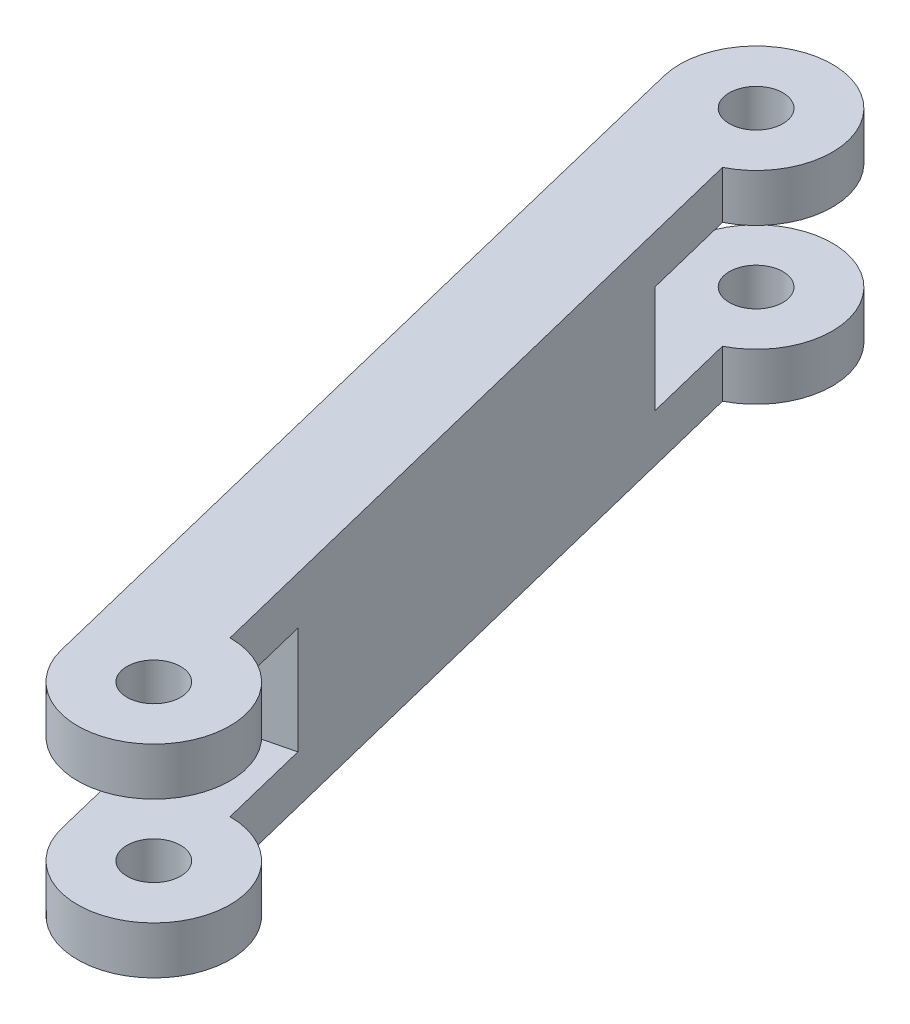
SolidWorks part; units mm, degrees
ref_plane "Front Plane" through (0, 0, 0) normal (0, 0, 1) x (1, 0, 0)
ref_plane "Top Plane" through (0, 0, 0) normal (0, 1, 0) x (1, 0, 0)
ref_plane "Right Plane" through (0, 0, 0) normal (1, 0, 0) x (0, 0, -1)
sketch "Sketch1" plane through (0, 0, 0) normal (0, 1, 0) x (1, 0, 0)
  line L0 (47.2297, 219.0186) -> (732.563, 219.0186) construction
  line L1 (-11.6924, 36.0113) -> (-3.4806, 2.5204)
  line L2 (-7.1402, 33.9178) -> (-0.3727, 6.4825)
  circle A0 centre (-8.5844, 36.7734) radius 1.125
  arc A1 (-7.1402, 33.9178) -> (-11.6924, 36.0113) centre (-8.5844, 36.7734) ccw
  circle A2 centre (-0.3727, 3.2825) radius 1.125
  arc A3 (-3.4806, 2.5204) -> (-0.3727, 6.4825) centre (-0.3727, 3.2825) ccw
extrude "Boss-Extrude7" add sketch "Sketch1" along normal blind 8.5
sketch "Sketch6" plane through (-2.7003, 0, 0.6621) normal (-0.9712, 0, 0.2381) x (0.2381, 0, 0.9712)
  line L0 (-37.7597, 8.5) -> (-3.2768, 8.5) construction
  line L1 (-30.7597, 6.5) -> (-46.7367, 6.5)
  line L2 (-30.7597, 6.5) -> (-30.7597, 2)
  line L3 (-30.7597, 2) -> (-46.7367, 2)
  line L4 (-46.7367, 6.5) -> (-46.7367, 2)
  line L5 (-37.7597, 8.5) -> (-37.7597, 0) construction
  line L6 (-3.2768, 8.5) -> (-3.2768, 0) construction
  line L7 (-10.2768, 6.5) -> (5.7134, 6.5)
  line L8 (-10.2768, 6.5) -> (-10.2768, 2)
  line L9 (-10.2768, 2) -> (5.7134, 2)
  line L10 (5.7134, 6.5) -> (5.7134, 2)
  dimension "D1" = 4.5
  dimension "D2" = 2
  dimension "D3" = 7
  dimension "D4" = 7
extrude "Cut-Extrude3" cut sketch "Sketch6" against normal blind 8.5
